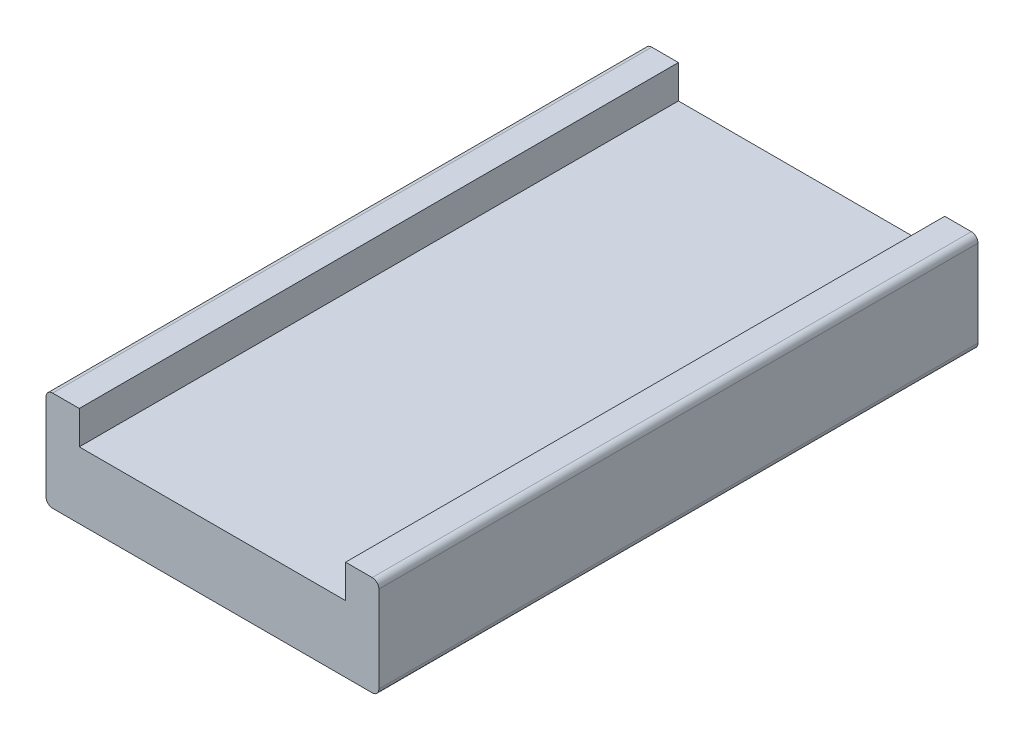
SolidWorks part; units mm, degrees
ref_plane "Front" through (0, 0, 0) normal (0, 0, 1) x (1, 0, 0)
ref_plane "Top" through (0, 0, 0) normal (0, 1, 0) x (1, 0, 0)
ref_plane "Right" through (0, 0, 0) normal (1, 0, 0) x (0, 0, -1)
sketch "Sketch1" plane through (0, 0, 0) normal (0, 0, 1) x (1, 0, 0)
  line L0 (-25, 0) -> (25, 0)
  line L1 (25, 0) -> (25, 15)
  line L2 (25, 15) -> (20, 15)
  line L3 (20, 15) -> (20, 10)
  line L4 (20, 10) -> (-20, 10)
  line L5 (-20, 10) -> (-20, 15)
  line L6 (-20, 15) -> (-25, 15)
  line L7 (-25, 15) -> (-25, 0)
  point P4 (0, 0)
  dimension "D1" = 50
  dimension "D2" = 15
  dimension "D3" = 15
  dimension "D4" = 5
  dimension "D5" = 5
  dimension "D6" = 5
  dimension "D7" = 0
extrude "Boss-Extrude1" add sketch "Sketch1" along normal blind 90
fillet "Fillet1" radius 1 4 edges at (25, 15, 45) (-25, 15, 45) (-25, 0, 45) (25, 0, 45)
